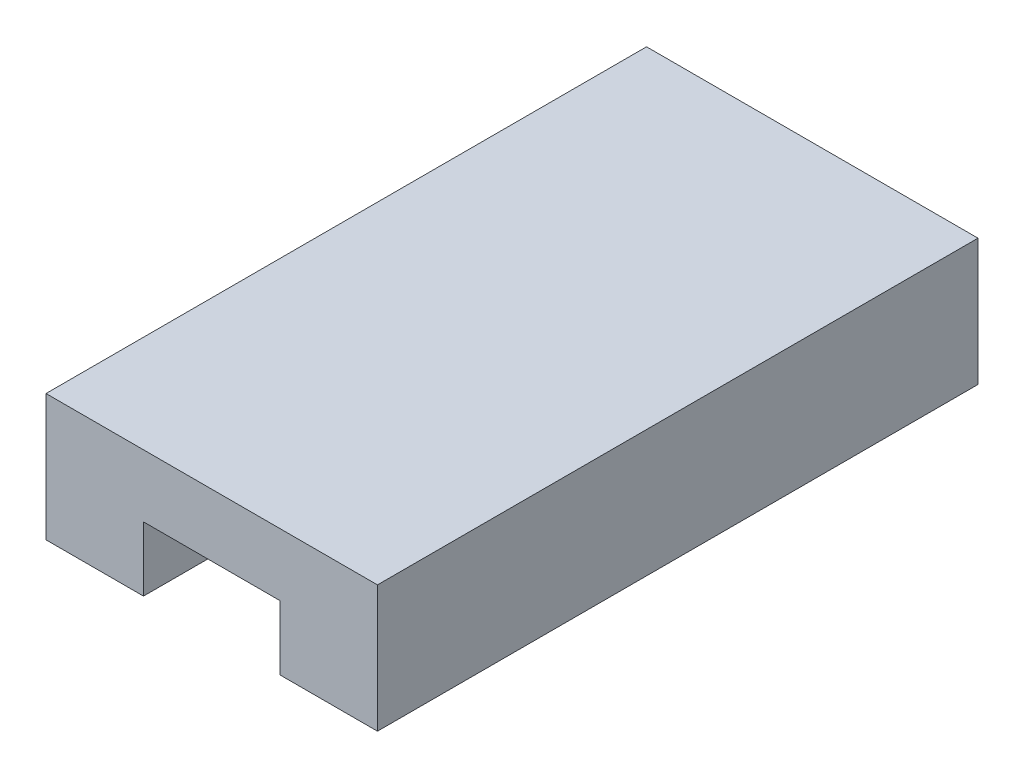
SolidWorks part; units mm, degrees
ref_plane "Front Plane" through (0, 0, 0) normal (0, 0, 1) x (1, 0, 0)
ref_plane "Top Plane" through (0, 0, 0) normal (0, 1, 0) x (1, 0, 0)
ref_plane "Right Plane" through (0, 0, 0) normal (1, 0, 0) x (0, 0, -1)
sketch "Sketch1" plane through (0, 0, 0) normal (0, 0, 1) x (1, 0, 0)
  line L0 (0, -30.2326) -> (0, 30.2326) construction
  line L1 (3.5, -2.4) -> (-3.5, -2.4)
  line L2 (3.5, -2.4) -> (3.5, 2.4)
  line L3 (3.5, 2.4) -> (-3.5, 2.4)
  line L4 (-3.5, -2.4) -> (-3.5, 2.4)
  line L5 (3.5, -2.4) -> (-3.5, 2.4) construction
  line L6 (3.5, 2.4) -> (-3.5, -2.4) construction
  line L8 (8.5, -0.9) -> (-8.5, -0.9)
  line L9 (8.5, -0.9) -> (8.5, 5.6)
  line L10 (8.5, 5.6) -> (-8.5, 5.6)
  line L11 (-8.5, -0.9) -> (-8.5, 5.6)
  line L12 (8.5, -0.9) -> (-8.5, 5.6) construction
  line L13 (8.5, 5.6) -> (-8.5, -0.9) construction
  point P0 (0, 0)
  point P8 (0, 2.35)
  point P13 (0, 13)
  dimension "D1" = 7
  dimension "D2" = 1.5
  dimension "D3" = 4.8
  dimension "D4" = 8
  dimension "D5" = 17
extrude "Boss-Extrude1" add sketch "Sketch1" along normal mid plane 30.8
